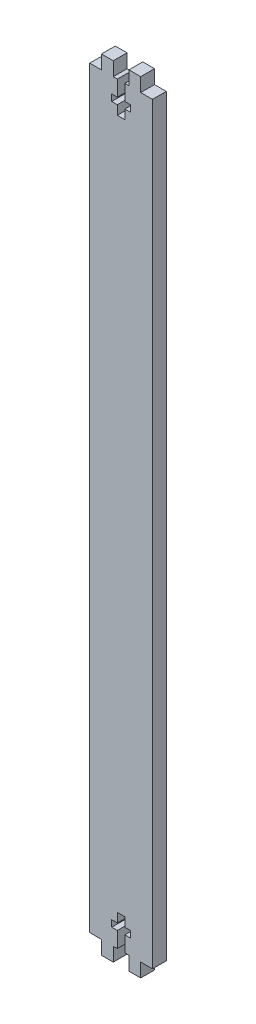
SolidWorks part; units mm, degrees
ref_plane "Front Plane" through (0, 0, 0) normal (0, 0, 1) x (1, 0, 0)
ref_plane "Top Plane" through (0, 0, 0) normal (0, 1, 0) x (1, 0, 0)
ref_plane "Right Plane" through (0, 0, 0) normal (1, 0, 0) x (0, 0, -1)
sketch "Sketch2" plane through (0, 0, 0) normal (0, 0, 1) x (1, 0, 0)
  line L1 (12.7, -157.988) -> (-12.7, -157.988)
  line L2 (12.7, -157.988) -> (12.7, 157.988)
  line L3 (12.7, 157.988) -> (-12.7, 157.988)
  line L4 (-12.7, -157.988) -> (-12.7, 157.988)
  line L5 (12.7, -157.988) -> (-12.7, 157.988) construction
  line L6 (12.7, 157.988) -> (-12.7, -157.988) construction
  point P0 (0, 0)
  dimension "D1" = 25.4
  dimension "12 in" = 315.976
extrude "Boss-Extrude1" add sketch "Sketch2" along normal blind 5.588 contours L4 L3 L2 L1
sketch "Sketch3" plane through (0, 0, 0) normal (0, 0, 1) x (1, 0, 0)
  line L0 (-12.7, -157.988) -> (-12.7, -152.4)
  line L1 (-12.7, -157.988) -> (-7.9375, -157.988)
  line L2 (-12.7, -152.4) -> (-7.9375, -152.4)
  line L3 (-7.9375, -157.988) -> (-7.9375, -152.4)
  line L4 (-12.7, -157.988) -> (-12.7, 157.988) construction
  line L5 (12.7, -157.988) -> (7.9375, -157.988)
  line L6 (12.7, -157.988) -> (12.7, -152.4)
  line L7 (7.9375, -157.988) -> (7.9375, -152.4)
  line L8 (12.7, -152.4) -> (7.9375, -152.4)
  line L10 (12.7, -157.988) -> (-12.7, -157.988) construction
  line L11 (3.175, -157.988) -> (3.175, -152.4)
  line L12 (3.175, -157.988) -> (-3.175, -157.988)
  line L13 (3.175, -152.4) -> (-3.175, -152.4)
  line L14 (-3.175, -157.988) -> (-3.175, -152.4)
  line L16 (-3.175, -155.194) -> (-7.9375, -155.194) construction
  line L17 (3.175, -155.194) -> (7.9375, -155.194) construction
  line L18 (-12.7, 157.988) -> (-12.7, 152.4)
  line L19 (-12.7, 157.988) -> (-7.9375, 157.988)
  line L20 (-12.7, 152.4) -> (-7.9375, 152.4)
  line L21 (-7.9375, 157.988) -> (-7.9375, 152.4)
  line L23 (-12.7, -157.988) -> (-12.7, 157.988) construction
  line L24 (12.7, 157.988) -> (12.7, 152.4)
  line L25 (12.7, 157.988) -> (7.9375, 157.988)
  line L26 (12.7, 152.4) -> (7.9375, 152.4)
  line L27 (7.9375, 157.988) -> (7.9375, 152.4)
  line L29 (12.7, -157.988) -> (12.7, 157.988) construction
  line L30 (-3.175, 157.988) -> (-3.175, 152.4)
  line L31 (-3.175, 157.988) -> (3.175, 157.988)
  line L32 (-3.175, 152.4) -> (3.175, 152.4)
  line L33 (3.175, 157.988) -> (3.175, 152.4)
  line L34 (12.7, 157.988) -> (-12.7, 157.988) construction
  point P15 (0, -157.988)
  dimension "D1" = 6.35
  dimension "D2" = 4.7625
  dimension "D3" = 5.588
extrude "Cut-Extrude2" cut sketch "Sketch3" along normal through all
sketch "Sketch4" plane through (0, 0, 0) normal (0, 0, 1) x (1, 0, 0)
  line L0 (-1.525, -152.4) -> (1.525, -152.4)
  line L1 (-1.525, -152.4) -> (-1.525, -139.7) construction
  line L2 (1.525, -152.4) -> (1.525, -139.7) construction
  line L3 (-1.525, -139.7) -> (1.525, -139.7)
  line L4 (3.175, -152.4) -> (-3.175, -152.4) construction
  line L5 (-3.79, -143.42) -> (-3.79, -146.05)
  line L6 (-3.79, -143.42) -> (3.79, -143.42) construction
  line L7 (-3.79, -146.05) -> (3.79, -146.05) construction
  line L8 (3.79, -143.42) -> (3.79, -146.05)
  line L9 (0, -146.05) -> (0, -152.4) construction
  line L10 (-1.525, -152.4) -> (-1.525, -146.05)
  line L11 (-1.525, -146.05) -> (-3.79, -146.05)
  line L12 (-3.79, -143.42) -> (-1.525, -143.42)
  line L13 (-1.525, -143.42) -> (-1.525, -139.7)
  line L14 (1.525, -139.7) -> (1.525, -143.42)
  line L15 (1.525, -143.42) -> (3.79, -143.42)
  line L16 (1.525, -152.4) -> (1.525, -146.05)
  line L17 (1.525, -146.05) -> (3.79, -146.05)
  point P6 (0, -152.4)
  dimension "D1" = 12.7
  dimension "D2" = 3.05
  dimension "D3" = 6.35
  dimension "D4" = 2.63
  dimension "D5" = 7.58
extrude "Cut-Extrude4" cut sketch "Sketch4" along normal through all
mirror "Mirror1" about plane through (0, 0, 0) normal (0, 1, 0) of "Cut-Extrude4"
